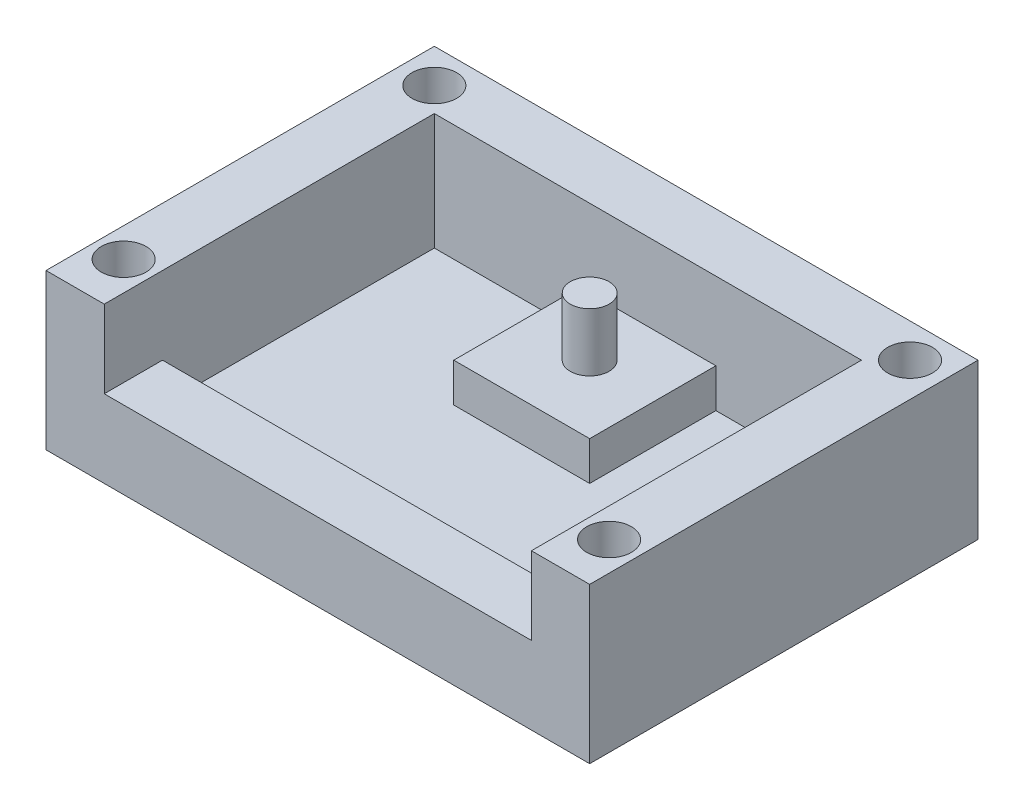
SolidWorks part; units mm, degrees
ref_plane "Plan de face" through (0, 0, 0) normal (0, 0, 1) x (1, 0, 0)
ref_plane "Plan de dessus" through (0, 0, 0) normal (0, 1, 0) x (1, 0, 0)
ref_plane "Plan de droite" through (0, 0, 0) normal (1, 0, 0) x (0, 0, -1)
sketch "Esquisse3" plane through (0, 0, 0) normal (0, 1, 0) x (1, 0, 0)
  line L1 (0, 0) -> (-28, 0)
  line L2 (0, 0) -> (0, -20)
  line L3 (0, -20) -> (-28, -20)
  line L4 (-28, 0) -> (-28, -20)
  dimension "D1" = 28
  dimension "D2" = 20
extrude "Boss.-Extru.1" add sketch "Esquisse3" along normal blind 8
sketch "Esquisse4" plane through (0, 8, 0) normal (0, 1, 0) x (1, 0, 0)
  line L8 (-3, -17) -> (-3, -3)
  line L9 (-3, -3) -> (-25, -3)
  line L10 (-25, -3) -> (-25, -17)
  line L11 (-25, -17) -> (-3, -17)
  line L12 (-3, -17) -> (-3, -3)
  line L13 (-3, -3) -> (-25, -3)
  line L14 (-25, -3) -> (-25, -17)
  line L15 (-25, -17) -> (-3, -17)
  dimension "D1" = 3
extrude "Enlèv. mat.-Extru.1" cut sketch "Esquisse4" against normal blind 6
sketch "Esquisse5" plane through (0, 8, 0) normal (0, 1, 0) x (1, 0, 0)
  line L0 (-28, -20) -> (0, -20) construction
  line L1 (-25, -17) -> (-3, -17)
  line L2 (-25, -17) -> (-25, -20)
  line L3 (-25, -20) -> (-3, -20)
  line L4 (-3, -17) -> (-3, -20)
  dimension "D1" = 22
extrude "Enlèv. mat.-Extru.2" cut sketch "Esquisse5" against normal blind 4
sketch "Esquisse7" plane through (0, 2, 0) normal (0, 1, 0) x (1, 0, 0)
  line L0 (-14, -20) -> (-14, -6) construction
  line L1 (-25, -20) -> (-3, -20) construction
  circle A1 centre (-14, -6) radius 1
  dimension "D2" = 2
  dimension "D1" = 14
extrude "Boss.-Extru.2" add sketch "Esquisse7" along normal blind 5
sketch "Esquisse9" plane through (0, 8, 0) normal (0, 1, 0) x (1, 0, 0)
  line L0 (0, 0) -> (-28, 0) construction
  line L2 (-28, 0) -> (-28, -20) construction
  circle A1 centre (-26.25, -1.75) radius 1.15
  dimension "D3" = 2.3
  dimension "D1" = 1.75
  dimension "D2" = 1.75
extrude "Enlèv. mat.-Extru.3" cut sketch "Esquisse9" against normal blind 2
ref_plane "coupe orthogonale par rapport a x" through (-14, 0, 0) normal (-1, 0, 0) x (0, 0, 1)
mirror "Symétrie1" about plane through (-14, 0, 0) normal (-1, 0, 0) of "Enlèv. mat.-Extru.3"
ref_plane "coupe orthogonale par rapport a z" through (0, 0, 10) normal (0, 0, -1) x (-1, 0, 0)
sketch "Esquisse11" plane through (0, 8, 0) normal (0, 1, 0) x (1, 0, 0)
  line L0 (-28, 0) -> (-28, -20) construction
  line L1 (-28, -20) -> (-25, -20) construction
  circle A0 centre (-26.5, -17.5) radius 1.15
  dimension "D1" = 2.3
  dimension "D2" = 1.5
  dimension "D3" = 2.5
extrude "Enlèv. mat.-Extru.4" cut sketch "Esquisse11" against normal blind 2
mirror "Symétrie2" about plane through (-14, 0, 0) normal (-1, 0, 0) of "Enlèv. mat.-Extru.4"
sketch "Esquisse12" plane through (0, 2, 0) normal (0, 1, 0) x (1, 0, 0)
  line L0 (-3, -3) -> (-25, -3) construction
  line L1 (-17.5, -3) -> (-10.5, -3)
  line L2 (-17.5, -3) -> (-17.5, -9.5)
  line L3 (-17.5, -9.5) -> (-10.5, -9.5)
  line L4 (-10.5, -3) -> (-10.5, -9.5)
  line L5 (-25, -3) -> (-25, -17) construction
  line L6 (-3, -17) -> (-3, -3) construction
  dimension "D1" = 7.5
  dimension "D2" = 7.5
  dimension "D3" = 6.5
extrude "Boss.-Extru.3" add sketch "Esquisse12" along normal blind 2
